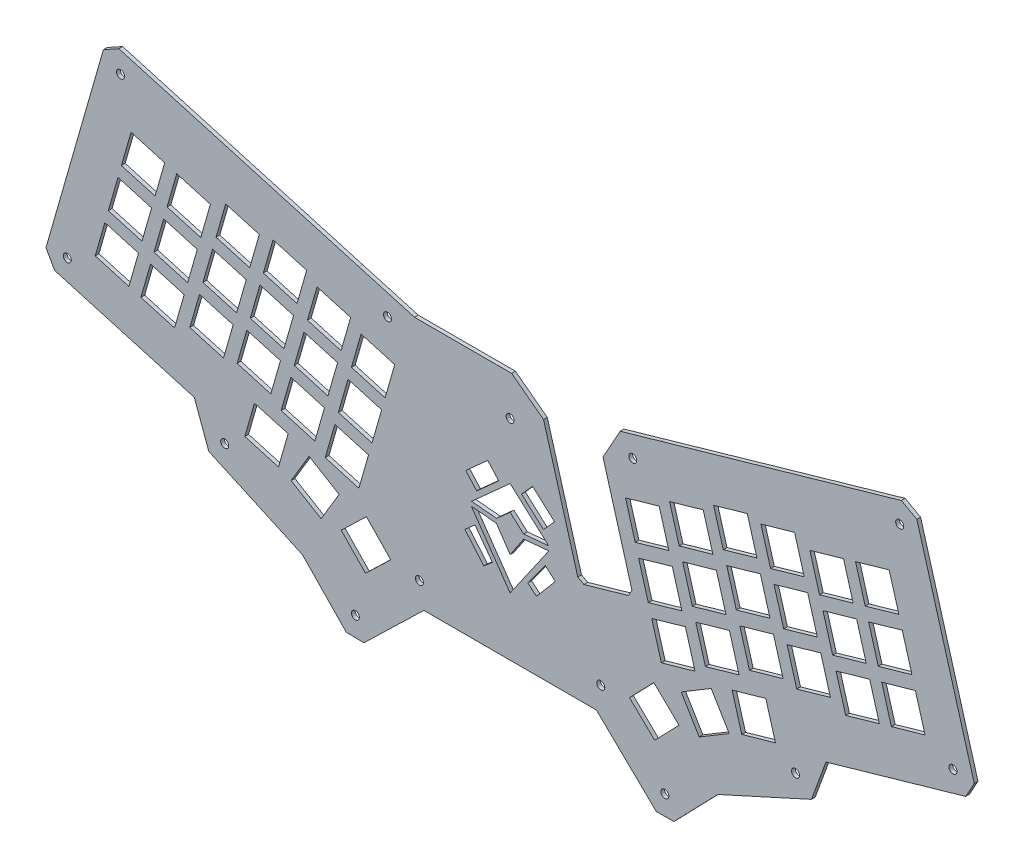
SolidWorks part; units mm, degrees
ref_plane "Plan de face" through (0, 0, 0) normal (0, 0, 1) x (1, 0, 0)
ref_plane "Plan de dessus" through (0, 0, 0) normal (0, 1, 0) x (1, 0, 0)
ref_plane "Plan de droite" through (0, 0, 0) normal (1, 0, 0) x (0, 0, -1)
sketch "Esquisse1" plane through (0, 0, 0) normal (0, 0, 1) x (1, 0, 0)
  line L0 (-121.6461, -32.0475) -> (-108.1875, -28.1884)
  line L1 (-108.1875, -28.1884) -> (-104.3283, -41.647)
  line L2 (-104.3283, -41.647) -> (-117.7869, -45.5062)
  line L3 (-117.7869, -45.5062) -> (-121.6461, -32.0475)
  line L4 (-100.1763, -37.9855) -> (-104.0355, -24.5269)
  line L5 (-104.0355, -24.5269) -> (-90.5769, -20.6677)
  line L6 (-90.5769, -20.6677) -> (-86.7177, -34.1263)
  line L7 (-86.7177, -34.1263) -> (-100.1763, -37.9855)
  line L8 (-82.5657, -30.4649) -> (-86.4249, -17.0063)
  line L9 (-86.4249, -17.0063) -> (-72.9663, -13.1471)
  line L10 (-72.9663, -13.1471) -> (-69.1071, -26.6057)
  line L11 (-69.1071, -26.6057) -> (-82.5657, -30.4649)
  line L12 (-63.6458, -27.5106) -> (-67.505, -14.0519)
  line L13 (-67.505, -14.0519) -> (-54.0463, -10.1927)
  line L14 (-54.0463, -10.1927) -> (-50.1872, -23.6514)
  line L15 (-50.1872, -23.6514) -> (-63.6458, -27.5106)
  line L16 (-44.0711, -26.8394) -> (-47.9303, -13.3808)
  line L17 (-47.9303, -13.3808) -> (-34.4717, -9.5216)
  line L18 (-34.4717, -9.5216) -> (-30.6125, -22.9802)
  line L19 (-30.6125, -22.9802) -> (-44.0711, -26.8394)
  line L20 (-25.8054, -21.6018) -> (-29.6646, -8.1432)
  line L21 (-29.6646, -8.1432) -> (-16.206, -4.284)
  line L22 (-16.206, -4.284) -> (-12.3468, -17.7426)
  line L23 (-12.3468, -17.7426) -> (-25.8054, -21.6018)
  line L24 (-116.4086, -50.3128) -> (-102.95, -46.4536)
  line L25 (-102.95, -46.4536) -> (-99.0908, -59.9122)
  line L26 (-99.0908, -59.9122) -> (-112.5494, -63.7714)
  line L27 (-112.5494, -63.7714) -> (-116.4086, -50.3128)
  line L28 (-98.798, -42.7922) -> (-85.3394, -38.933)
  line L29 (-85.3394, -38.933) -> (-81.4802, -52.3916)
  line L30 (-81.4802, -52.3916) -> (-94.9388, -56.2508)
  line L31 (-94.9388, -56.2508) -> (-98.798, -42.7922)
  line L32 (-81.1874, -35.2715) -> (-67.7288, -31.4123)
  line L33 (-67.7288, -31.4123) -> (-63.8696, -44.8709)
  line L34 (-63.8696, -44.8709) -> (-77.3282, -48.7301)
  line L35 (-77.3282, -48.7301) -> (-81.1874, -35.2715)
  line L36 (-62.2675, -32.3172) -> (-48.8089, -28.458)
  line L37 (-48.8089, -28.458) -> (-44.9497, -41.9166)
  line L38 (-44.9497, -41.9166) -> (-58.4083, -45.7758)
  line L39 (-58.4083, -45.7758) -> (-62.2675, -32.3172)
  line L40 (-42.6928, -31.646) -> (-29.2342, -27.7869)
  line L41 (-29.2342, -27.7869) -> (-25.375, -41.2455)
  line L42 (-25.375, -41.2455) -> (-38.8336, -45.1047)
  line L43 (-38.8336, -45.1047) -> (-42.6928, -31.646)
  line L44 (-24.4271, -26.4084) -> (-10.9685, -22.5492)
  line L45 (-10.9685, -22.5492) -> (-7.1093, -36.0078)
  line L46 (-7.1093, -36.0078) -> (-20.5679, -39.867)
  line L47 (-20.5679, -39.867) -> (-24.4271, -26.4084)
  line L48 (-19.1896, -44.6737) -> (-5.731, -40.8145)
  line L49 (-5.731, -40.8145) -> (-1.8718, -54.2731)
  line L50 (-1.8718, -54.2731) -> (-15.3304, -58.1323)
  line L51 (-15.3304, -58.1323) -> (-19.1896, -44.6737)
  line L52 (-37.4554, -49.9113) -> (-23.9967, -46.0521)
  line L53 (-23.9967, -46.0521) -> (-20.1376, -59.5107)
  line L54 (-20.1376, -59.5107) -> (-33.5962, -63.3699)
  line L55 (-33.5962, -63.3699) -> (-37.4554, -49.9113)
  line L56 (-57.03, -50.5825) -> (-43.5714, -46.7233)
  line L57 (-43.5714, -46.7233) -> (-39.7122, -60.1819)
  line L58 (-39.7122, -60.1819) -> (-53.1708, -64.0411)
  line L59 (-53.1708, -64.0411) -> (-57.03, -50.5825)
  line L60 (-75.9499, -53.5368) -> (-62.4913, -49.6776)
  line L61 (-62.4913, -49.6776) -> (-58.6321, -63.1362)
  line L62 (-58.6321, -63.1362) -> (-72.0908, -66.9954)
  line L63 (-72.0908, -66.9954) -> (-75.9499, -53.5368)
  line L64 (-93.5605, -61.0574) -> (-80.1019, -57.1982)
  line L65 (-80.1019, -57.1982) -> (-76.2427, -70.6569)
  line L66 (-76.2427, -70.6569) -> (-89.7013, -74.516)
  line L67 (-89.7013, -74.516) -> (-93.5605, -61.0574)
  line L68 (-111.1711, -68.5781) -> (-97.7125, -64.7189)
  line L69 (-97.7125, -64.7189) -> (-93.8533, -78.1775)
  line L70 (-93.8533, -78.1775) -> (-107.3119, -82.0367)
  line L71 (-107.3119, -82.0367) -> (-111.1711, -68.5781)
  line L72 (-79.0181, -77.3048) -> (-65.5595, -73.4456)
  line L73 (-65.5595, -73.4456) -> (-61.7003, -86.9042)
  line L74 (-61.7003, -86.9042) -> (-75.1589, -90.7634)
  line L75 (-75.1589, -90.7634) -> (-79.0181, -77.3048)
  line L76 (-99.4001, -88.1351) -> (-87.3916, -80.9362)
  line L77 (-87.3916, -80.9362) -> (-80.1927, -92.9448)
  line L78 (-80.1927, -92.9448) -> (-92.2012, -100.1436)
  line L79 (-92.2012, -100.1436) -> (-99.4001, -88.1351)
  line L80 (-120.0498, -100.4367) -> (-110.317, -90.3719)
  line L81 (-110.317, -90.3719) -> (-100.2522, -100.1047)
  line L82 (-100.2522, -100.1047) -> (-109.985, -110.1695)
  line L83 (-109.985, -110.1695) -> (-120.0498, -100.4367)
  line L86 (0.634, -55.7756) -> (-52.9527, -71.1413) construction
  line L89 (-59.2205, -88.2424) -> (-52.9527, -71.1413) construction
  line L96 (-93.4066, -103.0586) -> (-59.4637, -88.3612) construction
  line L97 (-105.418, -115.2057) -> (-93.9754, -103.3509) construction
  line L98 (-126.5332, -96.9919) -> (-107.5003, -115.385) construction
  line L99 (-167.7972, -50.1766) -> (-183.2082, -64.014)
  line L100 (-106.3822, -25.4572) -> (-123.6848, -30.4187) construction
  line L101 (-72.1178, -10.6906) -> (-88.4663, -15.3784) construction
  line L102 (-53.2337, -7.6163) -> (-70.5393, -12.5786) construction
  line L103 (-33.6604, -6.9452) -> (-50.9661, -11.9075) construction
  line L104 (-15.3965, -1.7081) -> (-31.745, -6.396) construction
  line L105 (0.5403, -55.2132) -> (-14.6896, -2.0999) construction
  line L106 (-16.199, -60.6113) -> (0.1495, -55.9235) construction
  line L107 (-52.7198, -71.0835) -> (-18.1144, -61.1606) construction
  line L108 (-59.1184, -88.0534) -> (-52.9674, -71.2752) construction
  line L109 (-183.2082, -64.014) -> (-173.1824, -64.9357)
  line L113 (-102.2678, -134.438) -> (-84.7238, -116.3191)
  line L114 (-84.7238, -116.3191) -> (-47.2969, -99.2981)
  line L115 (-47.2969, -99.2981) -> (-41.4917, -83.4594)
  line L116 (14.3812, -67.4381) -> (-41.4917, -83.4594)
  line L117 (17.8093, -61.2536) -> (-5.1371, 18.7701)
  line L122 (-11.3217, 22.1985) -> (-107.4545, -5.3614)
  line L129 (-167.7953, -27.6055) -> (-167.7953, -64.7189) construction
  line L130 (-242.0685, -103.8419) -> (-276.37, -88.2424) construction
  line L131 (-229.5108, -116.8112) -> (-242.0685, -103.8419) construction
  line L138 (-208.9328, -96.8551) -> (-229.5108, -116.8112) construction
  line L139 (-225.5107, -79.6567) -> (-208.9328, -96.8551) construction
  line L140 (-109.3352, -134.5492) -> (-102.2678, -134.438)
  line L142 (-5.1371, 18.7701) -> (-11.3217, 22.1985)
  line L143 (-211.4691, -30.6868) -> (-225.5107, -79.6567) construction
  line L147 (-114.18, -7.2899) -> (-107.4545, -5.3614)
  line L148 (-114.18, -7.2899) -> (-123.7936, -10.0465)
  line L154 (-4.3102, 15.8863) -> (-127.3606, -19.3904) construction
  line L155 (-131.531, -101.8802) -> (-105.9239, -126.7133) construction
  line L156 (-105.9239, -126.7133) -> (-89.4162, -109.6646) construction
  line L157 (-127.3539, -97.573) -> (-106.0575, -118.2258) construction
  line L158 (-106.0575, -118.2258) -> (-92.9354, -104.6737) construction
  line L159 (-92.9354, -104.6737) -> (-58.4256, -88.9794) construction
  line L160 (-58.4256, -88.9794) -> (-52.1886, -71.9625) construction
  line L161 (1.8709, -56.4612) -> (-52.1886, -71.9625) construction
  line L162 (1.8709, -56.4612) -> (-14.1861, -0.4639) construction
  line L163 (-14.1861, -0.4639) -> (-50.7166, -10.9388) construction
  line L164 (-50.7166, -10.9388) -> (-52.026, -6.3725) construction
  line L165 (-52.026, -6.3725) -> (-70.2913, -11.61) construction
  line L166 (-70.2913, -11.61) -> (-70.911, -9.4488) construction
  line L167 (-70.911, -9.4488) -> (-90.1377, -14.9608) construction
  line L168 (-90.1377, -14.9608) -> (-89.5177, -17.1231) construction
  line L169 (-89.5177, -17.1231) -> (-107.783, -22.3606) construction
  line L170 (-107.783, -22.3606) -> (-107.0938, -24.7639) construction
  line L171 (-107.0938, -24.7639) -> (-125.3583, -30.0011) construction
  line L172 (-125.3583, -30.0011) -> (-111.0411, -79.9324) construction
  line L173 (-110.7998, -78.9627) -> (-127.3777, -96.1611) construction
  line L174 (-89.4162, -109.6646) -> (-53.6562, -93.4017) construction
  line L175 (-53.6562, -93.4017) -> (-47.6042, -76.8897) construction
  line L176 (9.2923, -60.5749) -> (-47.6042, -76.8897) construction
  line L177 (9.2923, -60.5749) -> (-12.0005, 13.6817) construction
  line L178 (-229.7336, -25.4495) -> (-211.4691, -30.6868) construction
  line L179 (-229.0444, -23.0462) -> (-229.7336, -25.4495) construction
  line L180 (-173.1824, -64.9357) -> (-167.7972, -60.1004)
  line L181 (-247.3097, -17.8087) -> (-229.0444, -23.0462) construction
  line L185 (17.8093, -61.2536) -> (14.3812, -67.4381)
  line L186 (-183.2987, -65.7677) -> (-173.2729, -66.6895)
  line L187 (-173.2729, -66.6895) -> (-167.8052, -74.7882)
  line L190 (-246.6897, -15.6465) -> (-247.3097, -17.8087) construction
  line L191 (-263.9939, -10.6857) -> (-246.6897, -15.6465) construction
  line L192 (-264.6136, -12.8469) -> (-263.9939, -10.6857) construction
  line L193 (-282.8789, -7.6094) -> (-264.6136, -12.8469) construction
  line L194 (-284.1883, -12.1757) -> (-282.8789, -7.6094) construction
  line L195 (-320.7188, -1.7008) -> (-284.1883, -12.1757) construction
  line L196 (-336.2245, -55.7756) -> (-320.7188, -1.7008) construction
  line L197 (-183.2987, -65.7677) -> (-167.8052, -88.0782)
  line L198 (-181.8414, -71.5322) -> (-174.8684, -81.0171)
  line L199 (-174.8684, -81.0171) -> (-178.3549, -83.9622)
  line L200 (-344.8828, -60.5749) -> (-323.5901, 13.6817) construction
  line L201 (-344.8828, -60.5749) -> (-287.9863, -76.8897) construction
  line L202 (-281.9343, -93.4017) -> (-287.9863, -76.8897) construction
  line L203 (-246.1743, -109.6646) -> (-281.9343, -93.4017) construction
  line L204 (-224.7907, -78.9627) -> (-208.2128, -96.1611) construction
  line L205 (-210.2322, -30.0011) -> (-224.5494, -79.9324) construction
  line L206 (-228.4967, -24.7639) -> (-210.2322, -30.0011) construction
  line L207 (-227.8075, -22.3606) -> (-228.4967, -24.7639) construction
  line L208 (-246.0728, -17.1231) -> (-227.8075, -22.3606) construction
  line L209 (-245.4528, -14.9608) -> (-246.0728, -17.1231) construction
  line L210 (-264.6796, -9.4488) -> (-245.4528, -14.9608) construction
  line L211 (-265.2993, -11.61) -> (-264.6796, -9.4488) construction
  line L212 (-283.5645, -6.3725) -> (-265.2993, -11.61) construction
  line L213 (-284.8739, -10.9388) -> (-283.5645, -6.3725) construction
  line L217 (0.634, -55.7756) -> (-14.8717, -1.7008) construction
  line L220 (-14.8717, -1.7008) -> (-51.4022, -12.1757) construction
  line L221 (-51.4022, -12.1757) -> (-52.7116, -7.6094) construction
  line L222 (-52.7116, -7.6094) -> (-70.9769, -12.8469) construction
  line L223 (-70.9769, -12.8469) -> (-71.5966, -10.6857) construction
  line L224 (-71.5966, -10.6857) -> (-88.9008, -15.6465) construction
  line L225 (-88.9008, -15.6465) -> (-88.2808, -17.8087) construction
  line L226 (-88.2808, -17.8087) -> (-106.5461, -23.0462) construction
  line L227 (-106.5461, -23.0462) -> (-105.8569, -25.4495) construction
  line L228 (-105.8569, -25.4495) -> (-124.1214, -30.6868) construction
  line L231 (-124.1214, -30.6868) -> (-110.0799, -79.6567) construction
  line L232 (-110.0799, -79.6567) -> (-126.6577, -96.8551) construction
  line L233 (-126.6577, -96.8551) -> (-106.0797, -116.8112) construction
  line L234 (-106.0797, -116.8112) -> (-93.522, -103.8419) construction
  line L235 (-93.522, -103.8419) -> (-59.2205, -88.2424) construction
  line L236 (-321.4044, -0.4639) -> (-284.8739, -10.9388) construction
  line L237 (-337.4614, -56.4612) -> (-321.4044, -0.4639) construction
  line L238 (-337.4614, -56.4612) -> (-283.4019, -71.9625) construction
  line L239 (-277.1649, -88.9794) -> (-283.4019, -71.9625) construction
  line L240 (-242.6551, -104.6737) -> (-277.1649, -88.9794) construction
  line L241 (-229.5331, -118.2258) -> (-242.6551, -104.6737) construction
  line L242 (-208.2366, -97.573) -> (-229.5331, -118.2258) construction
  line L243 (-229.6666, -126.7133) -> (-246.1743, -109.6646) construction
  line L244 (-204.0596, -101.8802) -> (-229.6666, -126.7133) construction
  line L245 (-331.2803, 15.8863) -> (-208.2299, -19.3904) construction
  line L246 (-178.3549, -83.9622) -> (-185.8788, -75.0552)
  line L247 (-185.8788, -75.0552) -> (-181.8414, -71.5322)
  line L248 (-176.7625, -46.6332) -> (-185.5498, -54.5291)
  line L249 (-185.5498, -54.5291) -> (-181.1562, -59.4188)
  line L250 (-181.1562, -59.4188) -> (-172.3689, -51.5229)
  line L251 (-276.4721, -88.0534) -> (-282.6232, -71.2752) construction
  line L252 (-282.8707, -71.0835) -> (-317.4761, -61.1606) construction
  line L253 (-319.3915, -60.6113) -> (-335.74, -55.9235) construction
  line L254 (-336.1309, -55.2132) -> (-320.9009, -2.0999) construction
  line L255 (-320.194, -1.7081) -> (-303.8455, -6.396) construction
  line L256 (-301.9301, -6.9452) -> (-284.6245, -11.9075) construction
  line L257 (-282.3568, -7.6163) -> (-265.0512, -12.5786) construction
  line L258 (-263.4727, -10.6906) -> (-247.1242, -15.3784) construction
  line L259 (-229.2083, -25.4572) -> (-211.9057, -30.4187) construction
  line L260 (-172.3689, -51.5229) -> (-176.7625, -46.6332)
  line L261 (-209.0573, -96.9919) -> (-228.0902, -115.385) construction
  line L262 (-230.1725, -115.2057) -> (-241.6151, -103.3509) construction
  line L263 (-242.1839, -103.0586) -> (-276.1268, -88.3612) construction
  line L264 (-276.37, -88.2424) -> (-282.6379, -71.1413) construction
  line L265 (-336.2245, -55.7756) -> (-282.6379, -71.1413) construction
  line L268 (-353.3998, -61.2536) -> (-349.9717, -67.4381)
  line L274 (-221.4105, -7.2899) -> (-206.0252, -11.7015)
  line L275 (-221.4105, -7.2899) -> (-228.136, -5.3614)
  line L276 (-330.4534, 18.7701) -> (-324.2688, 22.1985)
  line L277 (-226.2553, -134.5492) -> (-233.3227, -134.438)
  line L281 (-324.2688, 22.1985) -> (-228.136, -5.3614)
  line L282 (-353.3998, -61.2536) -> (-330.4534, 18.7701)
  line L283 (-349.9717, -67.4381) -> (-294.0988, -83.4594)
  line L284 (-288.2936, -99.2981) -> (-294.0988, -83.4594)
  line L285 (-250.8667, -116.3191) -> (-288.2936, -99.2981)
  line L286 (-233.3227, -134.438) -> (-250.8667, -116.3191)
  line L288 (-225.6055, -110.1695) -> (-215.5407, -100.4367)
  line L289 (-235.3383, -100.1047) -> (-225.6055, -110.1695)
  line L290 (-225.2735, -90.3719) -> (-235.3383, -100.1047)
  line L291 (-215.5407, -100.4367) -> (-225.2735, -90.3719)
  line L292 (-243.3893, -100.1436) -> (-236.1904, -88.1351)
  line L293 (-255.3978, -92.9448) -> (-243.3893, -100.1436)
  line L294 (-248.1989, -80.9362) -> (-255.3978, -92.9448)
  line L295 (-236.1904, -88.1351) -> (-248.1989, -80.9362)
  line L296 (-260.4316, -90.7634) -> (-256.5724, -77.3048)
  line L297 (-273.8902, -86.9042) -> (-260.4316, -90.7634)
  line L298 (-270.031, -73.4456) -> (-273.8902, -86.9042)
  line L299 (-256.5724, -77.3048) -> (-270.031, -73.4456)
  line L300 (-228.2786, -82.0367) -> (-224.4194, -68.5781)
  line L301 (-241.7372, -78.1775) -> (-228.2786, -82.0367)
  line L302 (-237.878, -64.7189) -> (-241.7372, -78.1775)
  line L303 (-224.4194, -68.5781) -> (-237.878, -64.7189)
  line L304 (-245.8892, -74.516) -> (-242.03, -61.0574)
  line L305 (-259.3478, -70.6569) -> (-245.8892, -74.516)
  line L306 (-255.4886, -57.1982) -> (-259.3478, -70.6569)
  line L307 (-242.03, -61.0574) -> (-255.4886, -57.1982)
  line L308 (-263.4998, -66.9954) -> (-259.6406, -53.5368)
  line L309 (-276.9584, -63.1362) -> (-263.4998, -66.9954)
  line L310 (-273.0992, -49.6776) -> (-276.9584, -63.1362)
  line L311 (-259.6406, -53.5368) -> (-273.0992, -49.6776)
  line L312 (-282.4197, -64.0411) -> (-278.5605, -50.5825)
  line L313 (-295.8783, -60.1819) -> (-282.4197, -64.0411)
  line L314 (-292.0191, -46.7233) -> (-295.8783, -60.1819)
  line L315 (-278.5605, -50.5825) -> (-292.0191, -46.7233)
  line L316 (-301.9944, -63.3699) -> (-298.1352, -49.9113)
  line L317 (-315.453, -59.5107) -> (-301.9944, -63.3699)
  line L318 (-311.5938, -46.0521) -> (-315.453, -59.5107)
  line L319 (-298.1352, -49.9113) -> (-311.5938, -46.0521)
  line L320 (-320.2601, -58.1323) -> (-316.4009, -44.6737)
  line L321 (-333.7187, -54.2731) -> (-320.2601, -58.1323)
  line L322 (-329.8595, -40.8145) -> (-333.7187, -54.2731)
  line L323 (-316.4009, -44.6737) -> (-329.8595, -40.8145)
  line L324 (-315.0226, -39.867) -> (-311.1634, -26.4084)
  line L325 (-328.4812, -36.0078) -> (-315.0226, -39.867)
  line L326 (-324.622, -22.5492) -> (-328.4812, -36.0078)
  line L327 (-311.1634, -26.4084) -> (-324.622, -22.5492)
  line L328 (-296.7569, -45.1047) -> (-292.8977, -31.646)
  line L329 (-310.2155, -41.2455) -> (-296.7569, -45.1047)
  line L330 (-306.3563, -27.7869) -> (-310.2155, -41.2455)
  line L331 (-292.8977, -31.646) -> (-306.3563, -27.7869)
  line L332 (-277.1822, -45.7758) -> (-273.323, -32.3172)
  line L333 (-290.6408, -41.9166) -> (-277.1822, -45.7758)
  line L334 (-286.7817, -28.458) -> (-290.6408, -41.9166)
  line L335 (-273.323, -32.3172) -> (-286.7817, -28.458)
  line L336 (-258.2623, -48.7301) -> (-254.4031, -35.2715)
  line L337 (-271.7209, -44.8709) -> (-258.2623, -48.7301)
  line L338 (-267.8617, -31.4123) -> (-271.7209, -44.8709)
  line L339 (-254.4031, -35.2715) -> (-267.8617, -31.4123)
  line L340 (-240.6517, -56.2508) -> (-236.7925, -42.7922)
  line L341 (-254.1103, -52.3916) -> (-240.6517, -56.2508)
  line L342 (-250.2511, -38.933) -> (-254.1103, -52.3916)
  line L343 (-236.7925, -42.7922) -> (-250.2511, -38.933)
  line L344 (-223.0411, -63.7714) -> (-219.1819, -50.3128)
  line L345 (-236.4997, -59.9122) -> (-223.0411, -63.7714)
  line L346 (-232.6405, -46.4536) -> (-236.4997, -59.9122)
  line L347 (-219.1819, -50.3128) -> (-232.6405, -46.4536)
  line L348 (-323.2438, -17.7426) -> (-309.7851, -21.6018)
  line L349 (-319.3846, -4.284) -> (-323.2438, -17.7426)
  line L350 (-305.926, -8.1432) -> (-319.3846, -4.284)
  line L351 (-309.7851, -21.6018) -> (-305.926, -8.1432)
  line L352 (-304.978, -22.9802) -> (-291.5194, -26.8394)
  line L353 (-301.1188, -9.5216) -> (-304.978, -22.9802)
  line L354 (-287.6602, -13.3808) -> (-301.1188, -9.5216)
  line L355 (-291.5194, -26.8394) -> (-287.6602, -13.3808)
  line L356 (-285.4034, -23.6514) -> (-271.9448, -27.5106)
  line L357 (-281.5442, -10.1927) -> (-285.4034, -23.6514)
  line L358 (-268.0856, -14.0519) -> (-281.5442, -10.1927)
  line L359 (-271.9448, -27.5106) -> (-268.0856, -14.0519)
  line L360 (-266.4834, -26.6057) -> (-253.0248, -30.4649)
  line L361 (-262.6242, -13.1471) -> (-266.4834, -26.6057)
  line L362 (-249.1656, -17.0063) -> (-262.6242, -13.1471)
  line L363 (-253.0248, -30.4649) -> (-249.1656, -17.0063)
  line L364 (-248.8728, -34.1263) -> (-235.4142, -37.9855)
  line L365 (-245.0136, -20.6677) -> (-248.8728, -34.1263)
  line L366 (-231.555, -24.5269) -> (-245.0136, -20.6677)
  line L367 (-235.4142, -37.9855) -> (-231.555, -24.5269)
  line L368 (-217.8036, -45.5062) -> (-213.9444, -32.0475)
  line L369 (-231.2622, -41.647) -> (-217.8036, -45.5062)
  line L370 (-227.4031, -28.1884) -> (-231.2622, -41.647)
  line L371 (-213.9444, -32.0475) -> (-227.4031, -28.1884)
  line L372 (-226.2553, -134.5492) -> (-202.2968, -111.3509)
  line L373 (-109.3352, -134.5492) -> (-133.2937, -111.3509)
  line L374 (-141.5559, -103.3509) -> (-194.0347, -103.3509) construction
  line L375 (-167.7972, -50.1766) -> (-152.3861, -64.014)
  line L376 (-162.4119, -64.9357) -> (-167.7972, -60.1004)
  line L377 (-162.3376, -66.6895) -> (-167.8052, -74.7882)
  line L378 (-152.3118, -65.7677) -> (-167.8052, -88.0782)
  line L379 (-163.2254, -51.5229) -> (-158.8318, -46.6332)
  line L380 (-154.4381, -59.4188) -> (-163.2254, -51.5229)
  line L381 (-150.0445, -54.5291) -> (-154.4381, -59.4188)
  line L382 (-158.8318, -46.6332) -> (-150.0445, -54.5291)
  line L383 (-149.7316, -75.0552) -> (-153.7691, -71.5322)
  line L384 (-157.2555, -83.9622) -> (-149.7316, -75.0552)
  line L385 (-160.742, -81.0171) -> (-157.2555, -83.9622)
  line L386 (-153.7691, -71.5322) -> (-160.742, -81.0171)
  line L387 (-152.3118, -65.7677) -> (-162.3376, -66.6895)
  line L388 (-152.3861, -64.014) -> (-162.4119, -64.9357)
  line L389 (-206.0252, -11.7015) -> (-129.5654, -11.7015) construction
  line L390 (-119.0708, -62.7964) -> (-130.6498, -22.4155)
  line L391 (-123.5545, -47.16) -> (-127.4136, -33.7014) construction
  line L392 (-120.442, -65.2702) -> (-138.2688, -70.3819)
  line L393 (-140.7426, -69.0107) -> (-154.4194, -21.3141)
  line L394 (-167.1758, -11.7015) -> (-206.0252, -11.7015)
  line L395 (-154.4194, -21.3141) -> (-167.1758, -11.7015)
  line L396 (-123.7936, -10.0465) -> (-130.6498, -22.4155)
  line L397 (-138.2688, -70.3819) -> (-140.7426, -69.0107)
  line L398 (-119.0708, -62.7964) -> (-120.442, -65.2702)
  line L399 (-129.5654, -11.7015) -> (-123.7936, -10.0465) construction
  line L400 (-133.2937, -111.3509) -> (-202.2968, -111.3509)
  line L401 (-141.5559, -111.3509) -> (-194.0347, -111.3509) construction
  circle A2 centre (-12.0005, 13.6817) radius 1.6
  circle A3 centre (-12.0005, 13.6817) radius 3 construction
  circle A4 centre (-118.7579, -16.9241) radius 1.6
  circle A5 centre (9.2923, -60.5749) radius 1.6
  circle A6 centre (-53.6562, -93.4017) radius 1.6
  circle A7 centre (-105.9239, -126.7133) radius 1.6
  circle A8 centre (-131.531, -101.8802) radius 1.6
  circle A10 centre (-147.4897, -45.973) radius 1.6 construction
  circle A11 centre (-323.5901, 13.6817) radius 3 construction
  circle A12 centre (-188.1008, -45.973) radius 1.6 construction
  circle A14 centre (-204.0596, -101.8802) radius 1.6
  circle A15 centre (-229.6666, -126.7133) radius 1.6
  circle A16 centre (-281.9343, -93.4017) radius 1.6
  circle A17 centre (-344.8828, -60.5749) radius 1.6
  circle A18 centre (-216.8326, -16.9241) radius 1.6
  circle A19 centre (-323.5901, 13.6817) radius 1.6
  circle A20 centre (-167.7953, -27.6055) radius 1.6
  point P138 (-167.7953, -27.6055)
  point P139 (-6.5153, 23.5764)
  point P150 (-169.1046, -23.0392)
  point P200 (19.1875, -66.0599)
  point P203 (-141.5228, -71.3355)
  point P204 (-141.5228, 1.5705)
  point P263 (-133.4062, -12.8029)
  point P264 (-118.5195, -64.7189)
  point P283 (-140.1914, -70.9332)
  point P284 (-157.1758, -11.7015)
  point P405 (-354.778, -66.0599)
  point P406 (-329.0752, 23.5764)
  dimension "D3" = 3.2
  dimension "D4" = 6
  dimension "D6" = 3.2
  dimension "D7" = 3.2
  dimension "D8" = 3.2
  dimension "D9" = 3.2
  dimension "D10" = 3.2
  dimension "D16" = 3.2
  dimension "D2" = 6
  dimension "D5" = 8
extrude "Boss.-Extru.1" add sketch "Esquisse1" along normal blind 1.5
